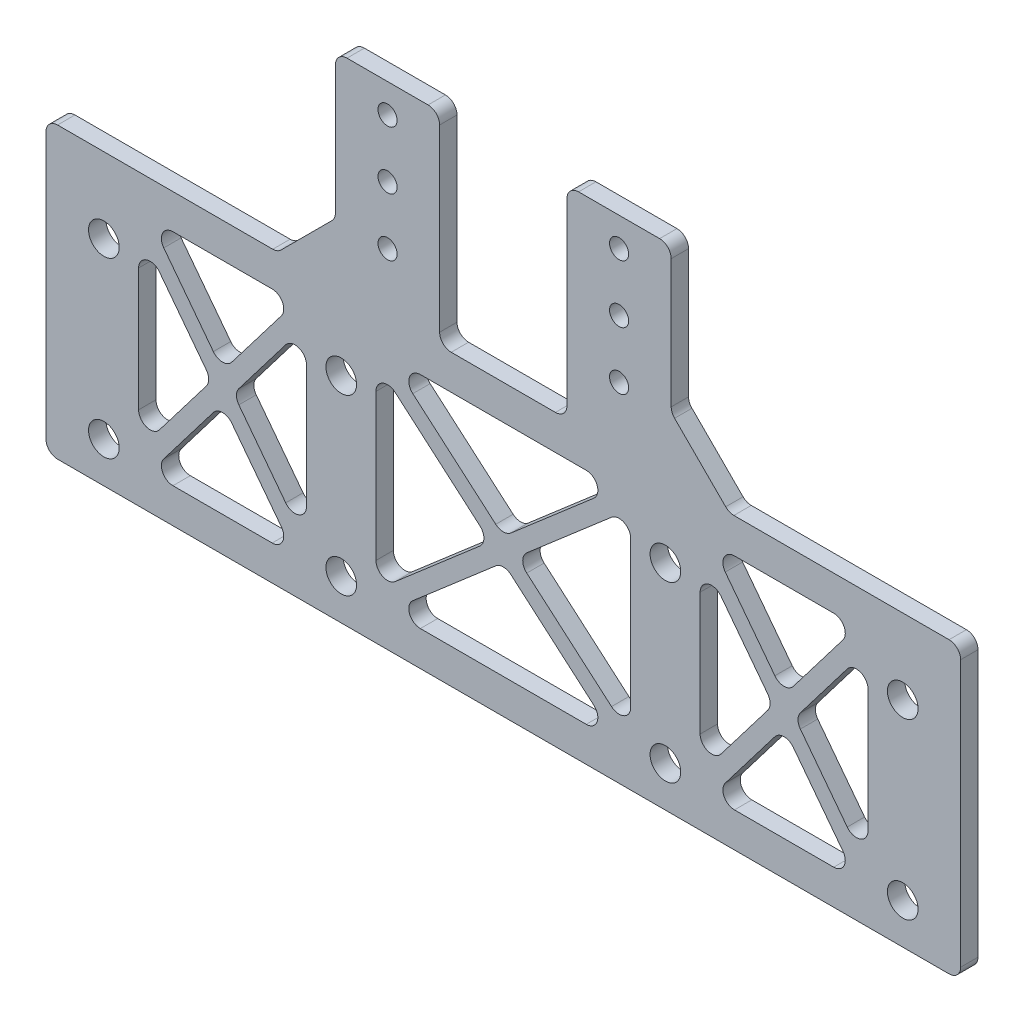
SolidWorks part; units mm, degrees
material "Thornel Mat VMA"
ref_plane "前视基准面" through (0, 0, 0) normal (0, 0, 1) x (1, 0, 0)
ref_plane "上视基准面" through (0, 0, 0) normal (0, 1, 0) x (1, 0, 0)
ref_plane "右视基准面" through (0, 0, 0) normal (1, 0, 0) x (0, 0, -1)
other "Configuration Table"
sketch "草图1" plane through (0, 0, 0) normal (0, 0, 1) x (1, 0, 0)
  line L0 (-10, 50) -> (-10, 85)
  line L1 (-10, 85) -> (10, 85)
  line L2 (-10, 50) -> (-79, 50)
  line L3 (-79, 50) -> (-79, 0)
  line L4 (0, 0) -> (0, 120.7371) construction
  line L5 (10, 50) -> (79, 50)
  line L6 (79, 50) -> (79, 0)
  line L7 (10, 50) -> (10, 85)
  line L8 (-79, 0) -> (79, 0)
  line L9 (-34, 6) -> (-34, 44)
  line L10 (63, 6) -> (34, 6)
  line L11 (63, 6) -> (63, 44)
  line L12 (63, 44) -> (34, 44)
  line L13 (34, 6) -> (34, 44)
  line L14 (63, 6) -> (34, 44) construction
  line L15 (63, 44) -> (34, 6) construction
  line L16 (22, 6) -> (-22, 6)
  line L17 (22, 6) -> (22, 44)
  line L18 (22, 44) -> (-22, 44)
  line L19 (-22, 6) -> (-22, 44)
  line L20 (22, 6) -> (-22, 44) construction
  line L21 (22, 44) -> (-22, 6) construction
  line L22 (-63, 6) -> (-34, 6)
  line L23 (-63, 6) -> (-63, 44)
  line L24 (-63, 44) -> (-34, 44)
  circle A0 centre (-6, 81) radius 1.55
  circle A1 centre (6, 81) radius 1.55
  circle A2 centre (-6, 59) radius 1.55
  circle A3 centre (6, 59) radius 1.55
  circle A4 centre (-69, 37) radius 2.65
  circle A5 centre (-69, 7) radius 2.65
  circle A6 centre (69, 7) radius 2.65
  circle A7 centre (69, 37) radius 2.65
  circle A8 centre (-28, 37) radius 2.65
  circle A9 centre (-28, 7) radius 2.65
  circle A10 centre (28, 7) radius 2.65
  circle A11 centre (28, 37) radius 2.65
  point P25 (48.5, 25)
  point P40 (0, 25)
  dimension "D3" = 3.1
  dimension "D4" = 4
  dimension "D5" = 22
  dimension "D6" = 4
  dimension "D8" = 30
  dimension "D10" = 5.3
  dimension "D11" = 138
  dimension "D12" = 41
  dimension "D14" = 6
  dimension "D1" = 85
  dimension "D2" = 35
  dimension "D7" = 20
  dimension "D9" = 13
  dimension "D13" = 10
  dimension "D15" = 6
  dimension "D16" = 6
  dimension "D17" = 6
  dimension "D18" = 6
  dimension "D19" = 6
  dimension "D20" = 6
extrude "凸台-拉伸1" add sketch "草图1" along normal blind 3
sketch "草图4" plane through (0, 0, 0) normal (0, 0, -1) x (-1, 0, 0)
  line L1 (-10, 85) -> (10, 85)
  line L2 (-10, 85) -> (-10, 50)
  line L3 (-10, 50) -> (10, 50)
  line L4 (10, 85) -> (10, 50)
  line L5 (-10, 85) -> (10, 50) construction
  line L6 (-10, 50) -> (10, 85) construction
  point P4 (0, 67.5)
extrude "切除-拉伸1" cut sketch "草图4" against normal blind 10
sketch "草图3" plane through (0, 0, 0) normal (0, 0, -1) x (-1, 0, 0)
  line L0 (0, 0) -> (0, 107.6848) construction
  line L1 (-79, 50) -> (79, 50) construction
  line L2 (-29, 85) -> (-11, 85)
  line L3 (-29, 85) -> (-29, 50)
  line L4 (-29, 50) -> (-11, 50)
  line L5 (-11, 85) -> (-11, 50)
  line L6 (-29, 85) -> (-11, 50) construction
  line L7 (-29, 50) -> (-11, 85) construction
  line L8 (29, 50) -> (11, 50)
  line L9 (11, 85) -> (11, 50)
  line L10 (29, 85) -> (11, 85)
  line L11 (29, 85) -> (29, 50)
  line L12 (29, 50) -> (11, 85) construction
  line L13 (29, 85) -> (11, 50) construction
  point P3 (-20, 67.5)
  point P14 (20, 67.5)
  dimension "D1" = 22
  dimension "D2" = 18
  dimension "D3" = 35
extrude "凸台-拉伸2" add sketch "草图3" against normal blind 3
sketch "草图5" plane through (0, 0, 0) normal (0, 0, -1) x (-1, 0, 0)
  line L0 (-20, 85) -> (-20, 49.8355) construction
  line L1 (-11, 85) -> (-29, 85) construction
  line L2 (-11, 50) -> (-11, 85) construction
  line L3 (-20, 80) -> (-20, 70) construction
  line L4 (0, 0) -> (0, 108.4309) construction
  circle A0 centre (-20, 80) radius 1.65
  circle A1 centre (-20, 70) radius 1.65
  circle A2 centre (-20, 60) radius 1.65
  circle A5 centre (20, 60) radius 1.65
  circle A6 centre (20, 70) radius 1.65
  circle A7 centre (20, 80) radius 1.65
  dimension "D5" = 3.3
  dimension "D1" = 9
  dimension "D2" = 5
  dimension "D4" = 10
  dimension "D3" = 3
extrude "切除-拉伸2" cut sketch "草图5" against normal blind 5
chamfer "倒角1" distance 10 angle 45 2 edges at (29, 50, 1.5) (-29, 50, 1.5)
fillet "圆角1" radius 2 14 edges at (79, 50, 1.5) (79, 0, 1.5) (-79, 0, 1.5) (-79, 50, 1.5) (11, 85, 1.5) (11, 50, 1.5) (29, 85, 1.5) (-29, 85, 1.5) (-11, 50, 1.5) (-11, 85, 1.5) (-39, 50, 1.5) (-29, 60, 1.5) (29, 60, 1.5) (39, 50, 1.5)
sketch "草图6" plane through (0, 0, 0) normal (0, 0, -1) x (-1, 0, 0)
  line L0 (-63, 44) -> (-34, 6)
  line L1 (-34, 44) -> (-63, 6)
  line L2 (-22, 44) -> (22, 6)
  line L3 (22, 44) -> (-22, 6)
  line L4 (34, 44) -> (63, 6)
  line L5 (63, 44) -> (34, 6)
  line L6 (63, 6) -> (34, 6) construction
  line L7 (34, 6) -> (34, 44) construction
  point P25 (34, 6)
extrude "拉伸-薄壁1" add sketch "草图6" against normal blind 3 thin thin type mid plane wall 3
fillet "圆角3" radius 2 36 edges at (0, 23.018, 1.5) (19.7051, 6, 1.5) (-19.7051, 6, 1.5) (-22, 42.018, 1.5) (-2.2949, 25, 1.5) (-22, 7.982, 1.5) (22, 7.982, 1.5) (2.2949, 25, 1.5) (22, 42.018, 1.5) (0, 26.982, 1.5) (-19.7051, 44, 1.5) (19.7051, 44, 1.5) (48.5, 27.4725, 1.5) (35.8869, 44, 1.5) (61.1131, 44, 1.5) (63, 8.4725, 1.5) (50.3869, 25, 1.5) (34, 41.5275, 1.5) (46.6131, 25, 1.5) (34, 8.4725, 1.5) (48.5, 22.5275, 1.5) (61.1131, 6, 1.5) (35.8869, 6, 1.5) (-48.5, 27.4725, 1.5) (-61.1131, 44, 1.5) (-35.8869, 44, 1.5) (-34, 8.4725, 1.5) (-46.6131, 25, 1.5) (-34, 41.5275, 1.5) (-63, 41.5275, 1.5) (-50.3869, 25, 1.5) (-63, 8.4725, 1.5) (-48.5, 22.5275, 1.5) (-35.8869, 6, 1.5) (-61.1131, 6, 1.5) (63, 41.5275, 1.5)
